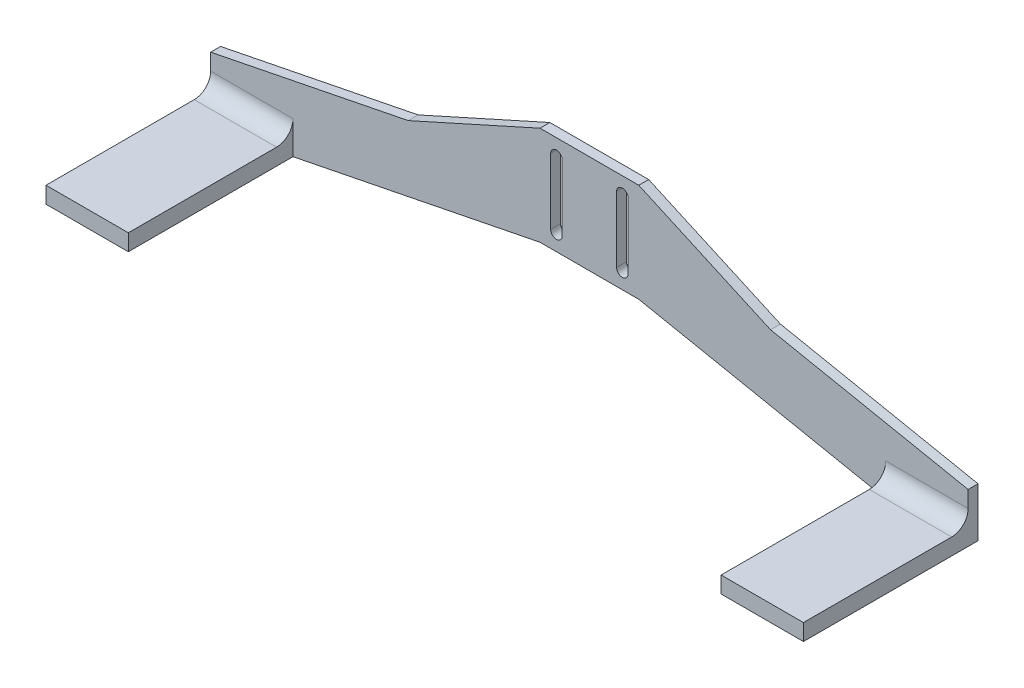
SolidWorks part; units mm, degrees
ref_plane "前视基准面" through (0, 0, 0) normal (0, 0, 1) x (1, 0, 0)
ref_plane "上视基准面" through (0, 0, 0) normal (0, 1, 0) x (1, 0, 0)
ref_plane "右视基准面" through (0, 0, 0) normal (1, 0, 0) x (0, 0, -1)
sketch "草图1" plane through (0, 0, 0) normal (0, 0, 1) x (1, 0, 0)
  line L0 (15, 0) -> (-15, 0) construction
  line L1 (-15, 15) -> (15, 15)
  line L2 (-15, 15) -> (-15, -15)
  line L3 (-15, -15) -> (15, -15)
  line L4 (15, 15) -> (15, -15)
  line L5 (-15, 15) -> (15, -15) construction
  line L6 (-15, -15) -> (15, 15) construction
  line L7 (-11.75, 10) -> (-8.25, 10)
  line L8 (-11.75, 10) -> (-11.75, -10)
  line L9 (-11.75, -10) -> (-8.25, -10)
  line L10 (-8.25, 10) -> (-8.25, -10)
  line L11 (-11.75, 10) -> (-8.25, -10) construction
  line L12 (-11.75, -10) -> (-8.25, 10) construction
  line L13 (11.75, 10) -> (8.25, 10)
  line L14 (11.75, 10) -> (11.75, -10)
  line L15 (11.75, -10) -> (8.25, -10)
  line L16 (8.25, 10) -> (8.25, -10)
  line L17 (11.75, 10) -> (8.25, -10) construction
  line L18 (11.75, -10) -> (8.25, 10) construction
  line L19 (-15, -15) -> (-90, -30)
  line L20 (-90, -30) -> (-115, -30)
  line L21 (-115, -30) -> (-115, -15)
  line L22 (-115, -15) -> (-55, -3)
  line L23 (-55, -3) -> (-15, 15)
  line L24 (0, 15) -> (0, -15) construction
  line L25 (55, -3) -> (15, 15)
  line L26 (115, -15) -> (55, -3)
  line L27 (115, -30) -> (115, -15)
  line L28 (90, -30) -> (115, -30)
  line L29 (15, -15) -> (90, -30)
  circle A0 centre (10, 10) radius 1.75
  circle A1 centre (10, -10) radius 1.75
  circle A2 centre (-10, -10) radius 1.75
  circle A3 centre (-10, 10) radius 1.75
  point P0 (0, 0)
  point P6 (-10, 0)
  point P11 (10, 0)
  point P19 (0, 0)
  point P34 (0, 0)
  point P38 (-32.3311, 1.896)
  point P39 (-68.3608, -5.0008)
  point P40 (-129.1421, -15)
  point P41 (-105.212, -30.9068)
  dimension "D1" = 30
  dimension "D2" = 30
  dimension "D3" = 3.5
  dimension "D4" = 3.5
  dimension "D5" = 20
  dimension "D6" = 20
  dimension "D7" = 5
  dimension "D8" = 5
  dimension "D9" = 25
  dimension "D10" = 15
  dimension "D11" = 15
  dimension "D12" = 75
  dimension "D13" = 40
extrude "凸台-拉伸1" add sketch "草图1" along normal blind 3 contours L4 L29 L28 L27 L26 L25 | L4 L1 L2 L3 A3 L10 A2 L8 A1 L16 A0 L14 | L23 L22 L21 L20 L19 L2
sketch "草图2" plane through (0, 0, 0) normal (0, 0, -1) x (-1, 0, 0)
  line L0 (-115, -30) -> (-90, -30)
  line L1 (-90, -30) -> (-90, -25)
  line L2 (-90, -25) -> (-115, -25)
  line L3 (-115, -30) -> (-115, -15) construction
  line L4 (-115, -25) -> (-115, -30)
  line L5 (115, -30) -> (115, -25)
  line L6 (115, -30) -> (115, -15) construction
  line L7 (115, -30) -> (90, -30)
  line L8 (90, -30) -> (90, -25)
  line L9 (90, -25) -> (115, -25)
  dimension "D1" = 5
  dimension "D2" = 5
extrude "凸台-拉伸2" add sketch "草图2" against normal blind 50 from offset 3 offset against normal yes
fillet "圆角1" radius 5 2 edges at (102.5, -25, 3) (-102.5, -25, 3)
equation "\"t\"=5.07997"
